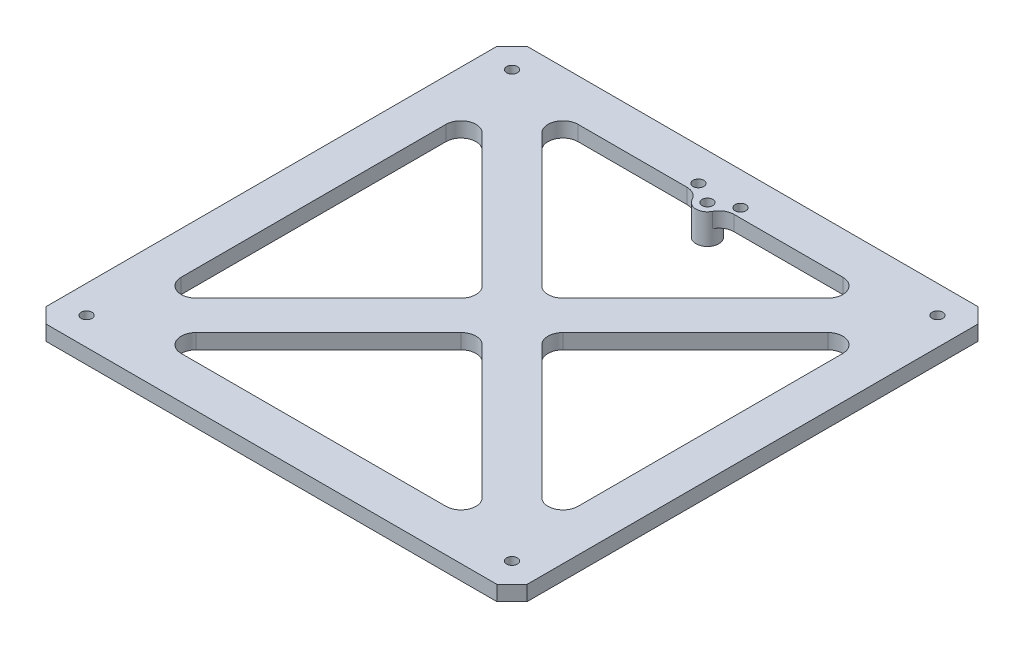
SolidWorks part; units mm, degrees
ref_plane "Front Plane" through (0, 0, 0) normal (0, 0, 1) x (1, 0, 0)
ref_plane "Top Plane" through (0, 0, 0) normal (0, 1, 0) x (1, 0, 0)
ref_plane "Right Plane" through (0, 0, 0) normal (1, 0, 0) x (0, 0, -1)
sketch "Sketch1" plane through (0, 0, 0) normal (0, 1, 0) x (1, 0, 0)
  line L0 (0, 196.85) -> (6.35, 203.2)
  line L1 (6.35, 0) -> (196.85, 0)
  line L2 (0, 6.35) -> (0, 196.85)
  line L3 (6.35, 203.2) -> (196.85, 203.2)
  line L4 (203.2, 6.35) -> (203.2, 196.85)
  line L5 (196.85, 203.2) -> (203.2, 196.85)
  line L6 (196.85, 0) -> (203.2, 6.35)
  line L7 (0, 6.35) -> (6.35, 0)
  point P0 (0, 0)
  point P1 (203.2, 203.2)
  point P2 (0, 203.2)
  point P3 (203.2, 0)
  dimension "D1" = 203.2
  dimension "D2" = 203.2
extrude "Boss-Extrude1" add sketch "Sketch1" along normal blind 6.35
sketch "Sketch2" plane through (0, 6.35, 0) normal (0, 1, 0) x (1, 0, 0)
  line L0 (203.2, 6.35) -> (203.2, 196.85) construction
  line L1 (45.6826, 185.42) -> (157.5174, 185.42)
  line L2 (17.78, 157.5174) -> (17.78, 45.6826)
  line L3 (45.6826, 17.78) -> (157.5174, 17.78)
  line L4 (185.42, 157.5174) -> (185.42, 45.6826)
  line L5 (196.85, 203.2) -> (6.35, 203.2) construction
  line L6 (0, 196.85) -> (0, 6.35) construction
  line L7 (3.175, 3.175) -> (200.025, 200.025) construction
  line L8 (3.175, 200.025) -> (101.6, 101.6) construction
  line L9 (28.6201, 162.0075) -> (84.5375, 106.0901)
  line L10 (41.1925, 28.6201) -> (97.1099, 84.5375)
  line L11 (41.1925, 174.5799) -> (97.1099, 118.6625)
  line L12 (28.6201, 41.1925) -> (84.5375, 97.1099)
  line L13 (9.4612, -3.1112) -> (206.3112, 193.7388) construction
  line L14 (-3.1112, 9.4612) -> (193.7388, 206.3112) construction
  line L15 (9.4612, 206.3112) -> (206.3112, 9.4612) construction
  line L16 (-3.1112, 193.7388) -> (193.7388, -3.1112) construction
  line L17 (118.6625, 106.0901) -> (174.5799, 162.0075)
  line L18 (101.6, 101.6) -> (200.025, 3.175) construction
  line L19 (3.175, 200.025) -> (200.025, 3.175) construction
  line L20 (118.6625, 97.1099) -> (174.5799, 41.1925)
  line L21 (106.0901, 118.6625) -> (162.0075, 174.5799)
  line L22 (106.0901, 84.5375) -> (162.0075, 28.6201)
  line L23 (6.35, 0) -> (196.85, 0) construction
  line L24 (6.35, 203.2) -> (0, 196.85) construction
  line L25 (203.2, 196.85) -> (196.85, 203.2) construction
  line L26 (196.85, 0) -> (203.2, 6.35) construction
  arc A0 (185.42, 45.6826) -> (174.5799, 41.1925) centre (179.07, 45.6826) cw
  arc A1 (185.42, 157.5174) -> (174.5799, 162.0075) centre (179.07, 157.5174) ccw
  arc A2 (157.5174, 185.42) -> (162.0075, 174.5799) centre (157.5174, 179.07) cw
  arc A3 (118.6625, 106.0901) -> (118.6625, 97.1099) centre (123.1526, 101.6) ccw
  arc A4 (41.1925, 28.6201) -> (45.6826, 17.78) centre (45.6826, 24.13) ccw
  arc A5 (157.5174, 17.78) -> (162.0075, 28.6201) centre (157.5174, 24.13) ccw
  arc A6 (28.6201, 41.1925) -> (17.78, 45.6826) centre (24.13, 45.6826) cw
  arc A7 (84.5375, 97.1099) -> (84.5375, 106.0901) centre (80.0474, 101.6) ccw
  arc A8 (28.6201, 162.0075) -> (17.78, 157.5174) centre (24.13, 157.5174) ccw
  arc A9 (41.1925, 174.5799) -> (45.6826, 185.42) centre (45.6826, 179.07) cw
  arc A10 (97.1099, 84.5375) -> (106.0901, 84.5375) centre (101.6, 80.0474) cw
  arc A11 (97.1099, 118.6625) -> (106.0901, 118.6625) centre (101.6, 123.1526) ccw
  point P10 (0, 101.6)
  point P11 (17.78, 101.6)
  point P37 (101.6, 17.78)
  point P40 (101.6, 101.6)
  point P50 (114.1724, 101.6)
  point P65 (101.6, 89.0276)
  point P68 (101.6, 114.1724)
  dimension "D7" = 6.35
  dimension "D8" = 6.35
  dimension "D9" = 6.35
  dimension "D1" = 17.78
  dimension "D2" = 17.78
  dimension "D3" = 8.89
  dimension "D5" = 17.78
  dimension "D6" = 17.78
  dimension "D4" = 8.89
extrude "Cut-Extrude1" cut sketch "Sketch2" against normal through all
sketch "Sketch3" plane through (0, 6.35, 0) normal (0, 1, 0) x (1, 0, 0)
  line L0 (6.35, 0) -> (196.85, 0) construction
  line L1 (0, 196.85) -> (0, 6.35) construction
  line L2 (203.2, 6.35) -> (203.2, 196.85) construction
  line L3 (196.85, 203.2) -> (6.35, 203.2) construction
  circle A0 centre (11.7373, 11.7373) radius 2.286
  circle A1 centre (191.4627, 11.7373) radius 2.286
  circle A2 centre (191.4627, 191.4627) radius 2.286
  circle A3 centre (11.7373, 191.4627) radius 2.286
  dimension "D1" = 2
  dimension "D3" = 4.572
  dimension "D4" = 11.7373
  dimension "D5" = 11.7373
  dimension "D6" = 11.7373
  dimension "D7" = 11.7373
  dimension "D8" = 11.7373
  dimension "D2" = 2
extrude "Cut-Extrude2" cut sketch "Sketch3" against normal through all
sketch "Sketch4" plane through (0, 6.35, 0) normal (0, 1, 0) x (1, 0, 0)
  line L0 (196.85, 203.2) -> (6.35, 203.2) construction
  line L1 (157.5174, 185.42) -> (45.6826, 185.42) construction
  line L3 (111.5547, 185.42) -> (91.6453, 185.42)
  circle A0 centre (101.6, 184.15) radius 2.286 construction
  arc A1 (97.3014, 181.9564) -> (105.8986, 181.9564) centre (101.6, 184.15) ccw
  arc A2 (97.3014, 181.9564) -> (91.6453, 185.42) centre (91.6453, 179.07) ccw
  arc A3 (111.5547, 185.42) -> (105.8986, 181.9564) centre (111.5547, 179.07) ccw
  point P5 (101.6, 203.2)
  dimension "D1" = 19.05
  dimension "D2" = 4.572
  dimension "D3" = 2.54
  dimension "D4" = 12.7
extrude "Boss-Extrude2" add sketch "Sketch4" against normal up to surface (6.35 mm away) up to face at (11.7373, 0, -189.1767)
sketch "Sketch5" plane through (0, 0, 0) normal (0, -1, 0) x (1, 0, 0)
  circle A0 centre (101.6, -184.15) radius 4.826
  arc A1 (105.8986, -181.9564) -> (97.3014, -181.9564) centre (101.6, -184.15) ccw construction
extrude "Boss-Extrude3" add sketch "Sketch5" along normal blind 6.35
sketch "Sketch6" plane through (0, -6.35, 0) normal (0, -1, 0) x (1, 0, 0)
  line L0 (92.71, -189.23) -> (110.49, -189.23) construction
  circle A0 centre (101.6, -184.15) radius 2.286
  circle A1 centre (92.71, -189.23) radius 2.286
  circle A2 centre (110.49, -189.23) radius 2.286
  point P7 (101.6, -189.23)
  dimension "D1" = 4.572
  dimension "D4" = 4.572
  dimension "D2" = 5.08
  dimension "D3" = 17.78
extrude "Cut-Extrude3" cut sketch "Sketch6" against normal through all contours A0 | A1 | A2
